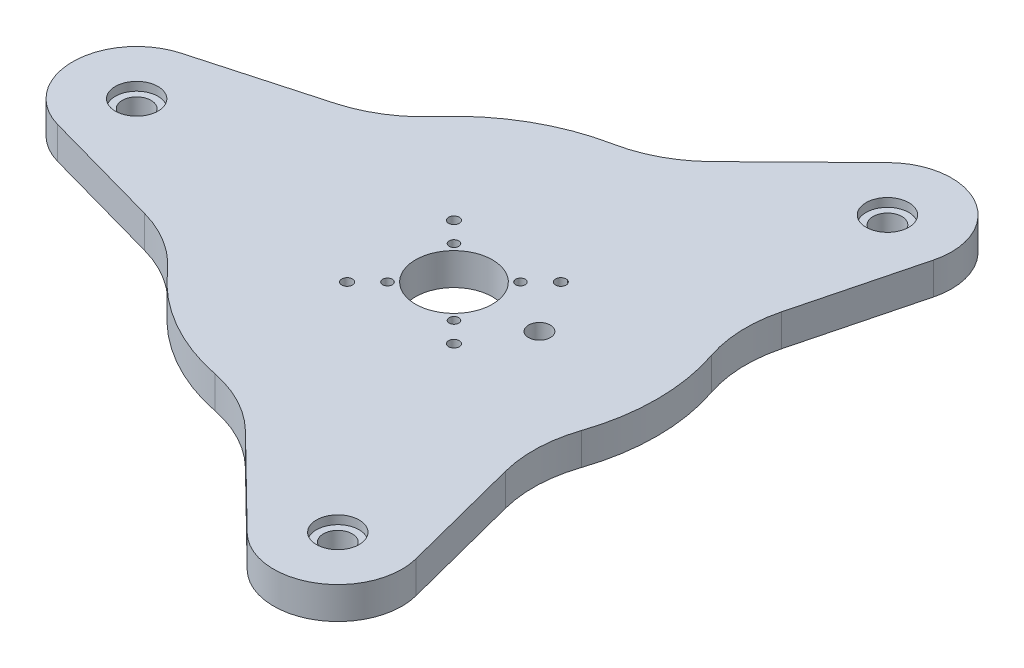
SolidWorks part; units mm, degrees
material "6063-T6"
ref_plane "Front Plane" through (0, 0, 0) normal (0, 0, 1) x (1, 0, 0)
ref_plane "Top Plane" through (0, 0, 0) normal (0, 1, 0) x (1, 0, 0)
ref_plane "Right Plane" through (0, 0, 0) normal (1, 0, 0) x (0, 0, -1)
sketch "Sketch1" plane through (0, 0, 0) normal (0, 1, 0) x (1, 0, 0)
  circle A0 centre (0, 0) radius 95
  dimension "D1" = 190
extrude "Boss-Extrude1" add sketch "Sketch1" along normal blind 15
sketch "Sketch2" plane through (0, 0, 0) normal (0, -1, 0) x (1, 0, 0)
  line L0 (0, 0) -> (-148.5, 0) construction
  line L1 (-156.5478, -28.9004) -> (-80.7775, -50)
  line L2 (-156.5478, 28.9004) -> (-80.7775, 50)
  circle A0 centre (-148.5, 0) radius 10
  arc A1 (-156.5478, 28.9004) -> (-156.5478, -28.9004) centre (-148.5, 0) ccw
  circle A2 centre (0, 0) radius 95 construction
  arc A3 (-80.7775, 50) -> (-80.7775, -50) centre (0, 0) ccw
  dimension "D2" = 20
  dimension "D3" = 60
  dimension "D1" = 148.5
  dimension "D4" = 100
extrude "Boss-Extrude2" add sketch "Sketch2" against normal up to surface (15 mm away) up to face at (0, 15, 95)
fillet "Fillet1" radius 60 2 edges at (-80.7775, 7.5, -50) (-80.7775, 7.5, 50)
sketch "Sketch4" plane through (0, 0, 0) normal (0, -1, 0) x (1, 0, 0)
  circle A0 centre (-148.5, 0) radius 10
  circle A1 centre (-148.5, 0) radius 10 construction
extrude "Boss-Extrude3" add sketch "Sketch4" against normal up to surface (11 mm away)
hole_wizard "M12 Clearance Hole1" positions "Sketch5" profile "Sketch6" hole size "M12" standard "ISO" end condition through all
sketch "Sketch5" plane through (0, 0, 0) normal (0, -1, 0) x (-1, 0, 0)
  point P0 (148.5, 0)
sketch "Sketch6" plane through (-148.5, 0, 0) normal (1, 0, 0) x (0, 0, -1)
  line L0 (0, 0) -> (0, 15)
  line L1 (0, 15) -> (6.75, 15)
  line L2 (6.75, 15) -> (6.75, 0)
  line L5 (6.75, 0) -> (0, 0)
  line L11 (0, -6.35) -> (0, 107.95) construction
  dimension "Thru Hole Dia." = 13.5
  dimension "Thru Hole Depth" = 15
pattern_circular "CirPattern1" count 3 over 360 about axis through (0, 0, 0) along (0, 1, 0) of "Fillet1", "Boss-Extrude2", "M12 Clearance Hole1", "Boss-Extrude3"
sketch "Sketch7" plane through (0, 0, 0) normal (0, -1, 0) x (-1, 0, 0)
  circle A0 centre (0, 0) radius 18
  dimension "D1" = 36
extrude "Cut-Extrude1" cut sketch "Sketch7" against normal through all
hole_wizard "M4 Clearance Hole1" positions "Sketch8" profile "Sketch9" hole size "M4" standard "ISO" end condition through all
sketch "Sketch8" plane through (0, 15, 0) normal (0, 1, 0) x (1, 0, 0)
  point P0 (-15.5563, -15.5563)
  point P3 (15.5563, -15.5563)
  point P6 (15.5563, 15.5563)
  point P9 (-15.5563, 15.5563)
sketch "Sketch9" plane through (-15.5563, 15, 15.5563) normal (1, 0, 0) x (0, 0, 1)
  line L0 (0, 0) -> (0, 15)
  line L1 (0, 15) -> (2.25, 15)
  line L2 (2.25, 15) -> (2.25, 0)
  line L5 (2.25, 0) -> (0, 0)
  line L11 (0, -6.35) -> (0, 107.95) construction
  dimension "Thru Hole Dia." = 4.5
  dimension "Thru Hole Depth" = 15
hole_wizard "M6 Tapped Hole1" positions "Sketch11" profile "Sketch12" tap size "M6" standard "ISO" end condition through all
sketch "Sketch11" plane through (0, 0, 0) normal (0, -1, 0) x (-1, 0, 0)
  line L1 (-25, -25) -> (25, -25)
  line L2 (-25, -25) -> (-25, 25)
  line L3 (-25, 25) -> (25, 25)
  line L4 (25, -25) -> (25, 25)
  line L5 (-25, -25) -> (25, 25) construction
  line L6 (-25, 25) -> (25, -25) construction
  point P1 (0, 0)
  point P2 (25, 25)
  point P47 (-25, -25)
  point P48 (-25, 25)
  point P49 (25, -25)
  dimension "D1" = 50
sketch "Sketch12" plane through (0, 0, 0) normal (1, 0, 0) x (0, 0, -1)
  line L0 (0, 0) -> (0, 15)
  line L1 (0, 15) -> (2.5, 15)
  line L2 (2.5, 15) -> (2.5, 0)
  line L5 (2.5, 0) -> (0, 0)
  line L11 (0, -6.35) -> (0, 107.95) construction
  dimension "Thru Tap Drill Dia." = 5
  dimension "Thru Tap Drill Depth" = 15
cosmetic thread "Hole Thread1" parameters "D2"=6
cosmetic thread "Hole Thread2" parameters "D2"=6
cosmetic thread "Hole Thread3" parameters "D2"=6
cosmetic thread "Hole Thread4" parameters "D2"=6
hole_wizard "M12 Tapped Hole1" positions "Sketch13" profile "Sketch14" tap size "M12" standard "ISO" end condition through all
sketch "Sketch13" plane through (0, 15, 0) normal (0, 1, 0) x (1, 0, 0)
  line L0 (0, 0) -> (40, 0) construction
  point P0 (40, 0)
  dimension "D1" = 40
sketch "Sketch14" plane through (40, 15, 0) normal (1, 0, 0) x (0, 0, 1)
  line L0 (0, 0) -> (0, 15)
  line L1 (0, 15) -> (5.1, 15)
  line L2 (5.1, 15) -> (5.1, 0)
  line L5 (5.1, 0) -> (0, 0)
  line L11 (0, -6.35) -> (0, 107.95) construction
  dimension "Thru Tap Drill Dia." = 10.2
  dimension "Thru Tap Drill Depth" = 15
cosmetic thread "Hole Thread5" parameters "D2"=12
